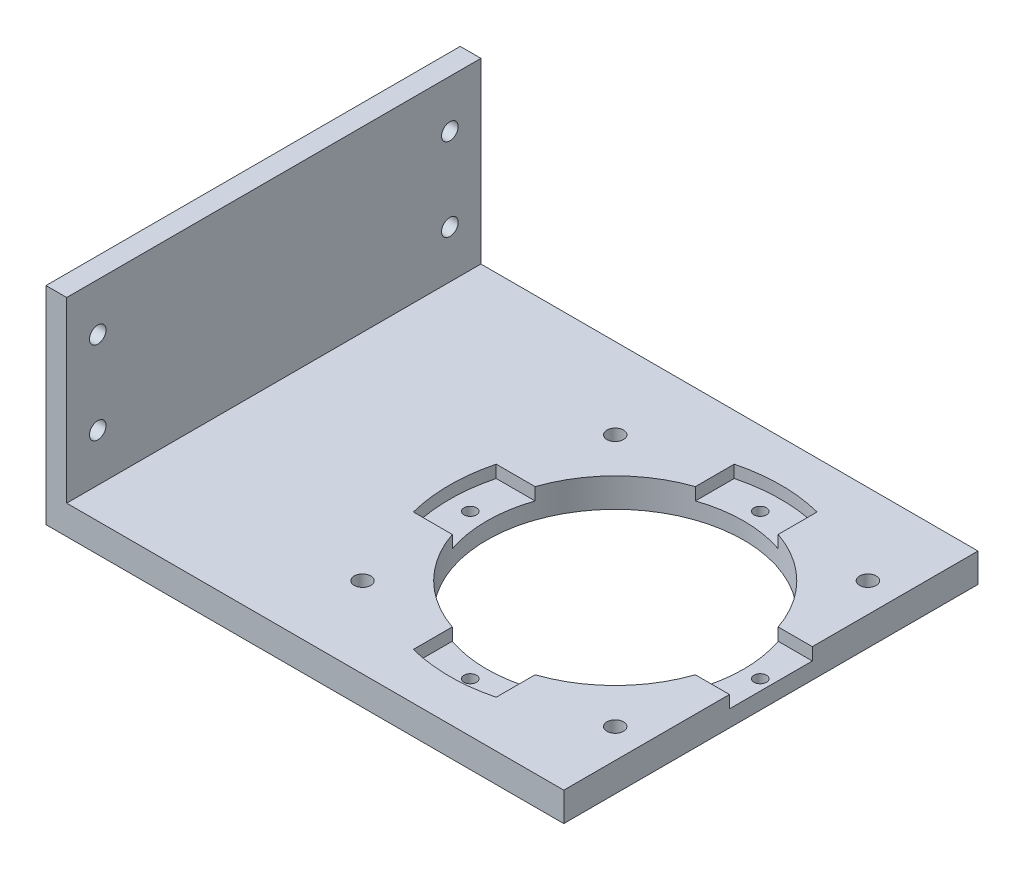
SolidWorks part; units mm, degrees
ref_plane "Front Plane" through (0, 0, 0) normal (0, 0, 1) x (1, 0, 0)
ref_plane "Top Plane" through (0, 0, 0) normal (0, 1, 0) x (1, 0, 0)
ref_plane "Right Plane" through (0, 0, 0) normal (1, 0, 0) x (0, 0, -1)
sketch "Sketch1" plane through (0, 0, 0) normal (0, 0, 1) x (1, 0, 0)
  line L0 (0, 0) -> (125, 0)
  line L1 (125, 0) -> (125, 7)
  line L2 (125, 7) -> (5, 7)
  line L3 (5, 7) -> (5, 50)
  line L4 (5, 50) -> (0, 50)
  line L5 (0, 50) -> (0, 0)
  dimension "D1" = 5
  dimension "D2" = 7
  dimension "D3" = 50
  dimension "D4" = 120
extrude "Boss-Extrude1" add sketch "Sketch1" along normal blind 100
sketch "Sketch2" plane through (0, 7, 0) normal (0, 1, 0) x (1, 0, 0)
  line L0 (5, -50) -> (125, -50) construction
  line L1 (5, -100) -> (5, 0) construction
  line L2 (125, -100) -> (125, 0) construction
  line L3 (0, -100) -> (0, 0) construction
  line L4 (87.42, -19) -> (87.42, -81) construction
  line L5 (117.92, -80.5) -> (56.92, -80.5) construction
  line L6 (117.92, -80.5) -> (117.92, -19.5) construction
  line L7 (117.92, -19.5) -> (56.92, -19.5) construction
  line L8 (56.92, -80.5) -> (56.92, -19.5) construction
  line L9 (117.92, -80.5) -> (56.92, -19.5) construction
  line L10 (117.92, -19.5) -> (56.92, -80.5) construction
  circle A0 centre (87.42, -50) radius 31
  circle A1 centre (56.92, -19.5) radius 2
  circle A2 centre (56.92, -80.5) radius 2
  circle A3 centre (117.92, -19.5) radius 2
  circle A4 centre (117.92, -80.5) radius 2
  dimension "D1" = 62
  dimension "D5" = 4
  dimension "D2" = 87.42
  dimension "D3" = 61
  dimension "D4" = 61
extrude "Cut-Extrude1" cut sketch "Sketch2" against normal up to next
sketch "Sketch3" plane through (5, 0, 0) normal (1, 0, 0) x (0, 0, -1)
  line L0 (-50, 50) -> (-50, 7) construction
  line L1 (-100, 50) -> (0, 50) construction
  line L2 (-100, 7) -> (0, 7) construction
  line L3 (-100, 28.5) -> (0, 28.5) construction
  line L4 (-100, 7) -> (-100, 50) construction
  line L5 (0, 7) -> (0, 50) construction
  circle A0 centre (-92.5, 38.5) radius 2
  circle A1 centre (-92.5, 18.5) radius 2
  circle A2 centre (-7.5, 38.5) radius 2
  circle A3 centre (-7.5, 18.5) radius 2
  dimension "D1" = 85
  dimension "D2" = 20
  dimension "D3" = 4
extrude "Cut-Extrude2" cut sketch "Sketch3" against normal up to next
sketch "Sketch4" plane through (0, 7, 0) normal (0, 1, 0) x (1, 0, 0)
  line L0 (87.42, -50) -> (87.42, -10) construction
  line L1 (97.42, -20.6572) -> (97.42, -11.2702)
  line L2 (77.42, -20.6572) -> (77.42, -11.2702)
  line L3 (97.42, -50) -> (97.42, -10) construction
  line L4 (77.42, -50) -> (77.42, -10) construction
  line L5 (116.7628, -60) -> (126.1498, -60)
  line L6 (116.7628, -40) -> (126.1498, -40)
  line L7 (77.42, -79.3428) -> (77.42, -88.7298)
  line L8 (97.42, -79.3428) -> (97.42, -88.7298)
  line L9 (58.0772, -40) -> (48.6902, -40)
  line L10 (58.0772, -60) -> (48.6902, -60)
  arc A0 (97.42, -11.2702) -> (77.42, -11.2702) centre (87.42, -50) ccw
  arc A1 (97.42, -20.6572) -> (77.42, -20.6572) centre (87.42, -50) ccw
  arc A2 (126.1498, -60) -> (126.1498, -40) centre (87.42, -50) ccw
  arc A3 (116.7628, -60) -> (116.7628, -40) centre (87.42, -50) ccw
  arc A4 (77.42, -88.7298) -> (97.42, -88.7298) centre (87.42, -50) ccw
  arc A5 (77.42, -79.3428) -> (97.42, -79.3428) centre (87.42, -50) ccw
  arc A6 (48.6902, -40) -> (48.6902, -60) centre (87.42, -50) ccw
  arc A7 (58.0772, -40) -> (58.0772, -60) centre (87.42, -50) ccw
  point P26 (87.42, -50)
  dimension "D1" = 80
  dimension "D2" = 10
  dimension "D3" = 10
  dimension "D4" = 4
extrude "Cut-Extrude3" cut sketch "Sketch4" against normal blind 3
sketch "Sketch6" plane through (0, 4, 0) normal (0, 1, 0) x (1, 0, 0)
  line L0 (87.42, -50) -> (87.42, -10) construction
  arc A0 (97.42, -11.2702) -> (77.42, -11.2702) centre (87.42, -50) ccw construction
  circle A1 centre (87.42, -15) radius 1.5
  circle A2 centre (122.42, -50) radius 1.5
  circle A3 centre (87.42, -85) radius 1.5
  circle A4 centre (52.42, -50) radius 1.5
  point P17 (87.42, -50)
  dimension "D1" = 35
  dimension "D2" = 3
extrude "Cut-Extrude4" cut sketch "Sketch6" against normal up to next
